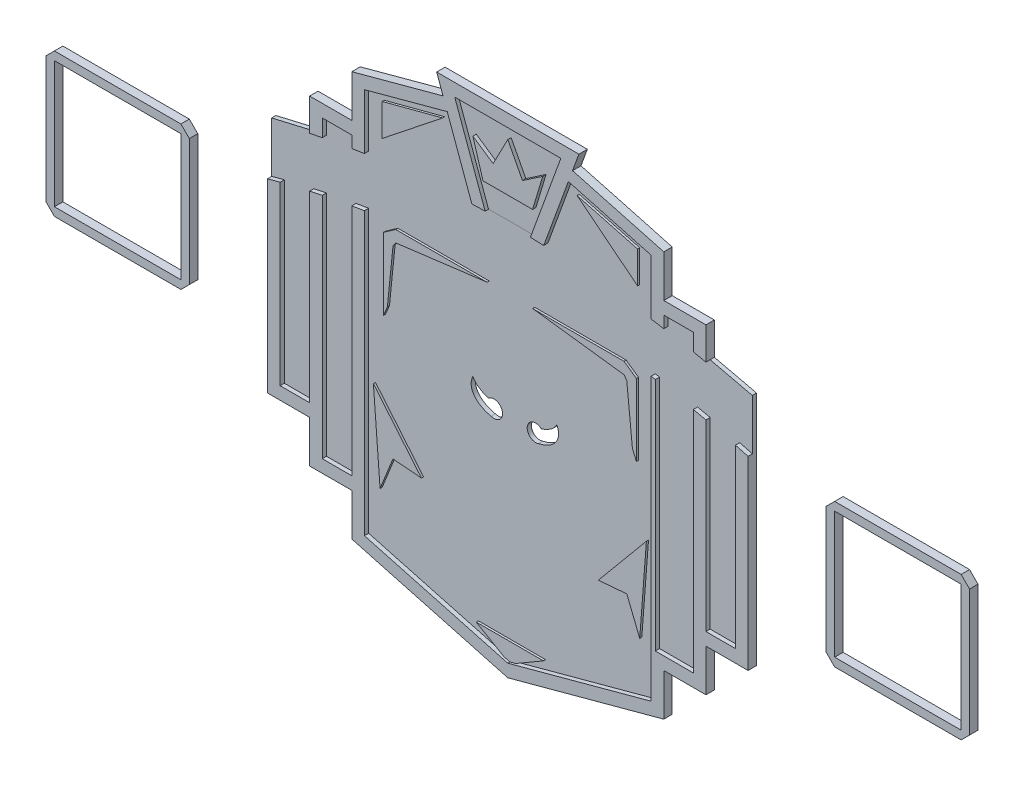
SolidWorks part; units mm, degrees
ref_plane "Alzado" through (0, 0, 0) normal (0, 0, 1) x (1, 0, 0)
ref_plane "Planta" through (0, 0, 0) normal (0, 1, 0) x (1, 0, 0)
ref_plane "Vista lateral" through (0, 0, 0) normal (1, 0, 0) x (0, 0, -1)
sketch "Croquis1" plane through (0, 0, 0) normal (0, 0, 1) x (1, 0, 0)
  line L0 (0, 29) -> (0, -29) construction
  line L1 (-18.5, 24) -> (18.5, 24) construction
  line L2 (-18.5, 24) -> (-18.5, -24)
  line L3 (-18.5, -24) -> (18.5, -24) construction
  line L4 (18.5, 24) -> (18.5, -24)
  line L5 (-18.5, 24) -> (18.5, -24) construction
  line L6 (-18.5, -24) -> (18.5, 24) construction
  line L7 (-18.5, -24) -> (0, -29)
  line L8 (18.5, -24) -> (0, -29)
  line L9 (-18.5, 24) -> (0, 29)
  line L10 (0, 29) -> (18.5, 24)
  point P0 (0, 0)
  point P9 (0, 0)
  point P11 (-15.5, -21.2436)
  dimension "D1" = 3
  dimension "D2" = 48
  dimension "D3" = 5
extrude "Saliente-Extruir1" add sketch "Croquis1" along normal blind 0.5
sketch "Croquis2" plane through (0, 0, 0.5) normal (0, 0, 1) x (1, 0, 0)
  line L0 (0, -29) -> (0, 29) construction
sketch "Croquis3" plane through (0, 0, 0) normal (0, 0, -1) x (-1, 0, 0)
  line L0 (-18.5, -24) -> (-18.5, 24) construction
  line L1 (23.5, 19) -> (-23.5, 19)
  line L2 (23.5, 19) -> (23.5, -19)
  line L3 (23.5, -19) -> (-23.5, -19)
  line L4 (-23.5, 19) -> (-23.5, -19)
  line L5 (23.5, 19) -> (-23.5, -19) construction
  line L6 (23.5, -19) -> (-23.5, 19) construction
  line L8 (28.5, 14) -> (-28.5, 14)
  line L9 (28.5, 14) -> (28.5, -14)
  line L10 (28.5, -14) -> (-28.5, -14)
  line L11 (-28.5, 14) -> (-28.5, -14)
  line L12 (28.5, 14) -> (-28.5, -14) construction
  line L13 (28.5, -14) -> (-28.5, 14) construction
  point P0 (0, 0)
  point P9 (0, 0)
  line M7 (18.5, -24) -> (18.5, 24)
  line M10 (-18.5, 24) -> (-18.5, -24)
  dimension "D1" = 5
  dimension "D2" = 5
  dimension "D3" = 5
  dimension "D4" = 5
extrude "Saliente-Extruir2" add sketch "Croquis3" against normal up to surface (0.5 mm away) contours L10 L8 M7 M10 | L8 L1 M7 M10 | L8 L2 L1 M7 | L8 L1 L4 M10 | L10 L8 L4 M10 | L10 L4 L3 M10 | L8 L11 L10 L4 | L10 L3 M7 M10 | L2 L10 L3 M7 | L10 L9 L8 L2 | L10 L2 L8 M7 up to face at (0, 0, 0.5)
sketch "Croquis4" plane through (0, 0, 0.5) normal (0, 0, 1) x (1, 0, 0)
  line L0 (-27, -12.5) -> (-27, 8.397)
  line L1 (-27, -12.5) -> (-23.5, -12.5)
  line L2 (-22, -12.5) -> (-22, -17.5)
  line L3 (-22, -17.5) -> (-18.5, -17.5)
  line L4 (-17, -17.5) -> (-17, -22.9054)
  line L5 (-17, -22.9054) -> (0, -27.5)
  line L6 (0, -29) -> (0, 29) construction
  line L7 (0, -27.5) -> (17, -22.9054)
  line L8 (17, -22.9054) -> (17, -17.5)
  line L9 (17.5, -17.5) -> (22, -17.5)
  line L10 (22, -17.5) -> (22, -12.5)
  line L11 (23.5, -12.5) -> (27, -12.5)
  line L12 (27, -12.5) -> (27, 8.397)
  line L13 (-22, 15.4736) -> (-22, 17.5)
  line L14 (-22, 17.5) -> (-18.5, 17.5)
  line L15 (-17, 17.5) -> (-17, 22.9054)
  line L16 (-17, 22.9054) -> (0, 27.5)
  line L17 (0, 27.5) -> (17, 22.9054)
  line L18 (17, 22.9054) -> (17, 17.5)
  line L19 (18.5, 17.5) -> (22, 17.5)
  line L20 (22, 17.5) -> (22, 15.4736)
  line L21 (0, -29) -> (18.5, -24) construction
  line L22 (-27, -12.5) -> (-28.5, -12.5) construction
  line L23 (-28.5, 14) -> (-28.5, -14) construction
  line L24 (-28.5, -12.5) -> (-23.5, -12.5) construction
  line L25 (-22, -17.5) -> (-22, -19) construction
  line L26 (-23.5, -19) -> (-18.5, -19) construction
  line L27 (-18.5, -19) -> (-17, -19) construction
  line L28 (-17, -19) -> (-17, -22.9054) construction
  line L29 (0, -27.5) -> (0, -29) construction
  line L30 (-23.5, -14) -> (-23.5, -12.5) construction
  line L31 (-22, -17.5) -> (-23.5, -17.5) construction
  line L32 (-23.5, -14) -> (-23.5, -19) construction
  line L33 (-22, 17.5) -> (-23.5, 17.5) construction
  line L34 (-23.5, 19) -> (-23.5, 14) construction
  line L35 (-23.5, 17.5) -> (-22, 17.5) construction
  line L36 (-22, 19) -> (-18.5, 19) construction
  line L37 (-23.5, 19) -> (-18.5, 19) construction
  line L38 (-18.5, 19) -> (-17, 19) construction
  line L39 (-23.5, -12.5) -> (-23.5, 9.2351)
  line L40 (-18.5, 19) -> (-18.5, 17.5) construction
  line L41 (-22, 19) -> (-22, 17.5) construction
  line L42 (0, 27.5) -> (0, 29) construction
  line L43 (0, 29) -> (-18.5, 24) construction
  line L44 (-28.5, 8) -> (-28.5, -14)
  line L45 (-28.5, -14) -> (-23.5, -14)
  line L46 (-23.5, -14) -> (-23.5, -19)
  line L47 (-23.5, -19) -> (-18.5, -19)
  line L48 (-18.5, -19) -> (-18.5, -24)
  line L49 (-18.5, -24) -> (0, -29)
  line L50 (0, -29) -> (18.5, -24)
  line L51 (18.5, -24) -> (18.5, -19)
  line L52 (18.5, -19) -> (23.5, -19)
  line L53 (23.5, -19) -> (23.5, -14)
  line L54 (23.5, -14) -> (28.5, -14)
  line L55 (28.5, -14) -> (28.5, 8)
  line L56 (28.5, 14) -> (28.5, -14) construction
  line L57 (-23.5, 15.1688) -> (-23.5, 19)
  line L58 (-23.5, 19) -> (-18.5, 19)
  line L59 (-18.5, 19) -> (-18.5, 24)
  line L60 (-18.5, 24) -> (0, 29)
  line L61 (0, 29) -> (18.5, 24)
  line L62 (18.5, 24) -> (18.5, 19)
  line L63 (18.5, 19) -> (23.5, 19)
  line L64 (23.5, 19) -> (23.5, 15.1688)
  line L65 (23.5, 19) -> (23.5, 14) construction
  line L66 (-22, -12.5) -> (-22, 9.5569)
  line L67 (-18.5, -17.5) -> (-18.5, 10.2222)
  line L68 (-17, -17.5) -> (-17, 10.4711)
  line L69 (-23.5, -12.5) -> (-22, -12.5) construction
  line L70 (-18.5, -17.5) -> (-17, -17.5) construction
  line L71 (-18.5, 17.5) -> (-18.5, 16.104)
  line L72 (-17, 17.5) -> (-17, 16.3399)
  line L73 (17, 17.5) -> (17, 16.3399)
  line L74 (18.5, 17.5) -> (18.5, 16.104)
  line L75 (23.5, -12.5) -> (23.5, 9.2351)
  line L76 (22, -12.5) -> (22, 9.5569)
  line L77 (17, -17.5) -> (17, 10.4711)
  line L78 (17.5, -17.5) -> (17.5, 10.3905)
  line L80 (-75, 75) -> (75, -75) construction
  line L81 (23.5, -12.5) -> (22, -12.5) construction
  line L82 (22, -17.5) -> (22, -19) construction
  line L83 (22, -19) -> (18.5, -19) construction
  line L84 (18.5, -19) -> (17.5, -17.5) construction
  arc A0 (28.5, 8) -> (-28.5, 8) centre (0, -96.6402) ccw construction
  arc A1 (28.5, 14) -> (-28.5, 14) centre (0, -96.6402) ccw construction
  arc A4 (-28.5, 8) -> (-27, 8.397) centre (0, -96.6402) cw
  arc A5 (27, 8.397) -> (28.5, 8) centre (0, -96.6402) cw
  arc A6 (-23.5, 15.1688) -> (-22, 15.4736) centre (0, -96.6402) cw
  arc A7 (22, 15.4736) -> (23.5, 15.1688) centre (0, -96.6402) cw
  arc A8 (-23.5, 9.2351) -> (-22, 9.5569) centre (0, -96.6402) cw
  arc A9 (-18.5, 10.2222) -> (-17, 10.4711) centre (0, -96.6402) cw
  arc A10 (-18.5, 16.104) -> (-17, 16.3399) centre (0, -96.6402) cw
  arc A11 (17, 16.3399) -> (18.5, 16.104) centre (0, -96.6402) cw
  arc A12 (22, 15.4736) -> (23.5, 15.1688) centre (0, -96.6402) cw
  arc A13 (-28.5, 8) -> (-27, 8.397) centre (0, -96.6402) cw
  arc A14 (-23.5, 9.2351) -> (-22, 9.5569) centre (0, -96.6402) cw
  arc A15 (-18.5, 10.2222) -> (-17, 10.4711) centre (0, -96.6402) cw
  arc A16 (17, 10.4711) -> (17.5, 10.3905) centre (0, -96.6402) cw
  arc A17 (22, 9.5569) -> (23.5, 9.2351) centre (0, -96.6402) cw
  arc A18 (27, 8.397) -> (28.5, 8) centre (0, -96.6402) cw
  line M48 (-18.5, 24) -> (-18.5, 19)
  line M49 (-18.5, 19) -> (-23.5, 19)
  line M50 (-23.5, 19) -> (-23.5, 14)
  line M52 (-28.5, 14) -> (-28.5, -14)
  line M53 (-28.5, -14) -> (-23.5, -14)
  line M54 (-23.5, -14) -> (-23.5, -19)
  line M55 (-23.5, -19) -> (-18.5, -19)
  line M56 (-18.5, -19) -> (-18.5, -24)
  line M57 (-18.5, -24) -> (0, -29)
  line M58 (0, -29) -> (18.5, -24)
  line M59 (18.5, -24) -> (18.5, -19)
  line M60 (18.5, -19) -> (23.5, -19)
  line M61 (23.5, -19) -> (23.5, -14)
  line M62 (23.5, -14) -> (28.5, -14)
  line M63 (28.5, -14) -> (28.5, 14)
  line M65 (23.5, 14) -> (23.5, 19)
  line M66 (23.5, 19) -> (18.5, 19)
  line M67 (18.5, 19) -> (18.5, 24)
  line M68 (18.5, 24) -> (0, 29)
  line M69 (0, 29) -> (-18.5, 24)
  dimension "D1" = 1.5
extrude "Saliente-Extruir3" add sketch "Croquis4" along normal blind 0.5 contours A17 L76 L10 L9 L78 A16 L77 L8 L7 L5 L4 L68 A9 L67 L3 L2 L66 A8 L39 L1 L0 A4 A5 L12 L11 L75 M52 M53 M54 M55 M56 M57 M58 M59 M60 M61 M62 M63 | L73 A11 L74 L19 L20 A7 A6 L13 L14 L71 A10 L72 L15 L16 L17 L18 M65 M66 M67 M68 M69 M48 M49 M50
sketch "Croquis5" plane through (0, 0, 0) normal (0, 0, -1) x (-1, 0, 0)
  line L0 (-28.5, 14) -> (-23.5, 14)
  line L1 (-23.5, 14) -> (-23.5, 15.1688)
  line L2 (-23.5, 15.1688) -> (-28.5, 14)
  line L3 (23.5, 15.1688) -> (23.5, 14)
  line L4 (23.5, 14) -> (28.5, 14)
  line L5 (28.5, 14) -> (23.5, 15.1688)
extrude "Saliente-Extruir4" add sketch "Croquis5" against normal up to surface (0.5 mm away) up to face at (-0.0476, 5.8126, 0.5)
sketch "Croquis6" plane through (0, 0, 0.5) normal (0, 0, 1) x (1, 0, 0)
  line L0 (0, 0) -> (0, 17.6117) construction
  line L1 (0, 17.6117) -> (0, 29) construction
  line L3 (-8.4351, 29) -> (8.4351, 29)
  line L4 (-8.4351, 29) -> (-4.2611, 17.5322)
  line L5 (8.4351, 29) -> (4.2611, 17.5322)
  arc A0 (28.5, 14) -> (-28.5, 14) centre (0, -96.6402) ccw construction
  arc A1 (-4.2611, 17.5322) -> (4.2611, 17.5322) centre (0, -96.6402) cw
  point P10 (0, 29)
  point P12 (0, 29)
  point P22 (0, 17.6117)
  dimension "D1" = 12.2037
  dimension "D2" = 70
extrude "Saliente-Extruir5" add sketch "Croquis6" along normal up to surface (0.5 mm away) up to face at (0, 19.2042, 1)
sketch "Croquis7" plane through (0, 0, 1) normal (0, 0, 1) x (1, 0, 0)
  line L0 (0, 29) -> (0, 17.6117) construction
  line L1 (8.4351, 29) -> (-8.4351, 29) construction
  line L2 (-6.2928, 27.5) -> (6.2928, 27.5)
  line L3 (6.2928, 27.5) -> (2.6823, 17.5802)
  line L4 (2.6823, 17.5802) -> (-2.6823, 17.5802)
  line L5 (-2.6823, 17.5802) -> (-6.2928, 27.5)
  line L6 (-7.1826, 25.5588) -> (-4.2611, 17.5322) construction
  line L7 (-4.4876, 22.5401) -> (-5.8971, 22.0271) construction
  line L8 (0, 27.5) -> (0, 29) construction
  line L9 (-6.2928, 27.5) -> (-6.2928, 29) construction
  line L10 (-2.9404, 20.5721) -> (2.9404, 20.5721)
  line L11 (2.9404, 20.5721) -> (4.1384, 24.5656)
  line L12 (4.1384, 24.5656) -> (1.7384, 22.9391)
  line L13 (1.7384, 22.9391) -> (0, 26.2807)
  line L14 (-2.9404, 20.5721) -> (-4.1384, 24.5656)
  line L15 (-4.1384, 24.5656) -> (-1.7384, 22.9391)
  line L16 (-1.7384, 22.9391) -> (0, 26.2807)
  arc A0 (4.2611, 17.5322) -> (-4.2611, 17.5322) centre (0, -96.6402) ccw construction
  point P10 (0, 27.5)
  point P21 (0, 20.5721)
  dimension "D1" = 1.5
extrude "Cortar-Extruir2" cut sketch "Croquis7" against normal blind 0.4
sketch "Croquis8" plane through (0, 0, 0.5) normal (0, 0, 1) x (1, 0, 0)
  line L0 (-15.1483, 22.4902) -> (-15.1483, 18.6908)
  line L1 (-15.1483, 18.6908) -> (-7.9716, 24.39)
  line L2 (-7.9716, 24.39) -> (-15.1483, 22.4902)
  line L5 (-15.0074, 9.1141) -> (-15.0074, 0.5805)
  line L8 (-16.1889, -7.0019) -> (-13.5291, -10.1999)
  line L9 (-13.5291, -10.1999) -> (-10.4878, -13.8564)
  line L10 (-10.4878, -13.8564) -> (-13.8675, -13.5744)
  line L11 (-13.8675, -13.5744) -> (-15.396, -17.3788)
  line L12 (-15.396, -17.3788) -> (-16.1889, -7.0019)
  line L14 (0, 0) -> (0, -25.393) construction
  line L21 (-15.0074, 0.5805) -> (-14.5284, 1.706)
  line L22 (-14.5284, 1.706) -> (-13.86, 8.3345)
  line L24 (-2.7, 10.1513) -> (-13.5379, 10.1513)
  line L25 (-13.5379, 10.1513) -> (-15.0074, 9.1141)
  line L26 (-13.86, 8.3345) -> (-13.5379, 8.7716)
  line L27 (-13.5379, 8.7716) -> (-2.7, 10.1513)
  line L28 (-3.9852, -25.393) -> (3.9852, -25.393)
  line L29 (3.9852, -25.393) -> (0, -27.7156)
  line L30 (0, -27.7156) -> (-3.9852, -25.393)
  line L31 (0, -25.393) -> (0, -27.7156) construction
  point P18 (0, -25.393)
extrude "Saliente-Extruir6" add sketch "Croquis8" along normal blind 0.25
mirror "Simetría1" about plane through (0, 0, 0) normal (1, 0, 0) of "Saliente-Extruir6"
sketch "Croquis9" plane through (0, 0, 0.5) normal (0, 0, -1) x (-1, 0, 0)
  line L0 (-8.4351, 29) -> (-7.6796, 26.9244)
  line L1 (-7.6796, 26.9244) -> (0, 29)
  line L2 (0, 29) -> (7.6796, 26.9244)
  line L3 (7.6796, 26.9244) -> (8.4351, 29)
  line L4 (8.4351, 29) -> (-8.4351, 29)
extrude "Saliente-Extruir7" add sketch "Croquis9" along normal up to surface (0.5 mm away) contours L1 L4 L0
sketch "Croquis10" plane through (0, 0, 0) normal (0, 0, 1) x (1, 0, 0)
  line L0 (0, 0) -> (-46.264, 0) construction
  line L1 (-46.264, 7.5) -> (-46.264, 10) construction
  line L2 (-53.764, 8.5) -> (-38.764, 8.5)
  line L3 (-54.764, 7.5) -> (-54.764, -7.5)
  line L4 (-53.764, -8.5) -> (-38.764, -8.5)
  line L5 (-37.764, 7.5) -> (-37.764, -7.5)
  line L6 (-54.764, 8.5) -> (-37.764, -8.5) construction
  line L7 (-54.764, -8.5) -> (-37.764, 8.5) construction
  line L8 (-53.764, 7.5) -> (-38.764, 7.5)
  line L9 (-53.764, 7.5) -> (-53.764, -7.5)
  line L10 (-53.764, -7.5) -> (-38.764, -7.5)
  line L11 (-38.764, 7.5) -> (-38.764, -7.5)
  line L12 (-53.764, 7.5) -> (-38.764, -7.5) construction
  line L13 (-53.764, -7.5) -> (-38.764, 7.5) construction
  line L14 (-54.764, 7.5) -> (-53.764, 8.5)
  line L15 (-38.764, 8.5) -> (-37.764, 7.5)
  line L16 (-38.764, -8.5) -> (-37.764, -7.5)
  line L17 (-54.764, -7.5) -> (-53.764, -8.5)
  dimension "D1" = 2.5
  dimension "D2" = 17
extrude "Saliente-Extruir8" add sketch "Croquis10" along normal up to surface (1 mm away) separate body up to face at (-0.0588, -8.5401, 1)
mirror "Simetría3" about plane through (0, 0, 0) normal (1, 0, 0) of bodies 111
sketch "Croquis12" plane through (0, 0, 0.5) normal (0, 0, 1) x (1, 0, 0)
  arc A0 (3.4721, -1.9435) -> (3.1591, -3.6183) centre (2.8009, -2.6847) ccw
  arc A1 (-2.4805, -3.6183) -> (-2.7936, -1.9435) centre (-2.1223, -2.6847) ccw
  spline S0 degree 3 poles (3.1591, -3.6183) (4.6578, -3.3142) (6.0407, -2.2116) (5.3252, -0.6099) knots 0 0 0 0 1 1 1 1
  spline S1 degree 3 poles (5.3252, -0.6099) (4.9959, -1.0644) (4.8675, -1.246) (3.9275, -1.8011) (3.8552, -1.8092) (3.4721, -1.9435) knots 0 0 0 0 0.376187 0.476187 1 1 1 1
  spline S2 degree 3 poles (-2.4805, -3.6183) (-3.9792, -3.3142) (-5.3622, -2.2116) (-4.6467, -0.6099) knots 0 0 0 0 1 1 1 1
  spline S3 degree 3 poles (-4.6467, -0.6099) (-4.3173, -1.0644) (-4.1889, -1.246) (-3.2489, -1.8011) (-3.1767, -1.8092) (-2.7936, -1.9435) knots 0 0 0 0 0.376187 0.476187 1 1 1 1
  point P8 (-2.1135, -2.6711)
  point P10 (2.8097, -2.6711)
extrude "Cortar-Extruir3" cut sketch "Croquis12" against normal through all both and the other way through all
